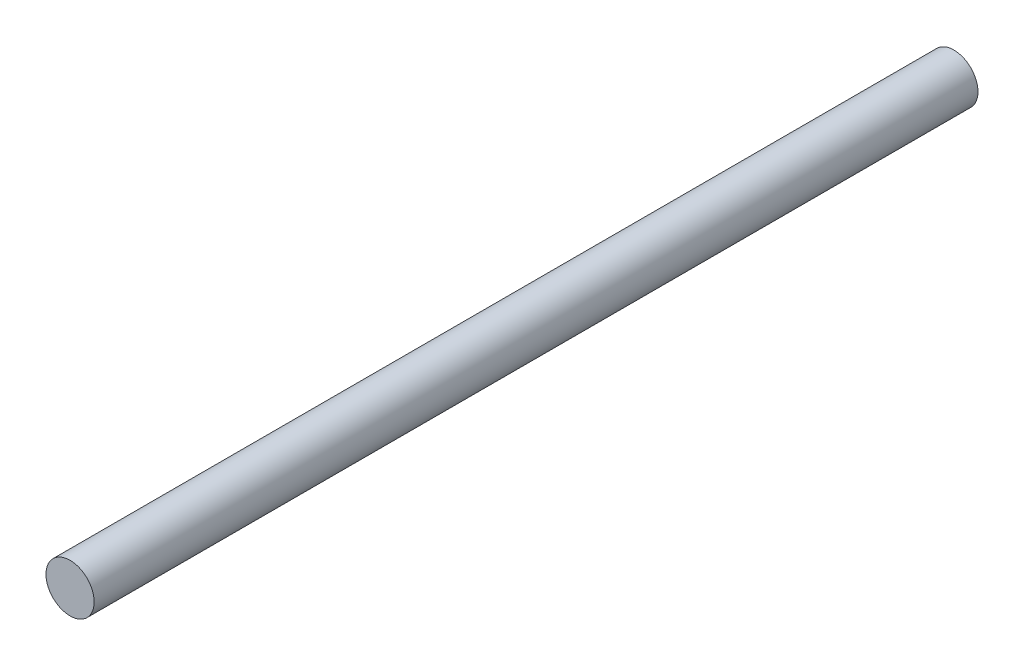
SolidWorks part; units mm, degrees
ref_plane "前基準面" through (0, 0, 0) normal (0, 0, 1) x (1, 0, 0)
ref_plane "上基準面" through (0, 0, 0) normal (0, 1, 0) x (1, 0, 0)
ref_plane "右基準面" through (0, 0, 0) normal (1, 0, 0) x (0, 0, -1)
sketch "草圖1" plane through (0, 0, 0) normal (0, 0, 1) x (1, 0, 0)
  circle A0 centre (0, 0) radius 3
  dimension "D1" = 6
extrude "填料-伸長1" add sketch "草圖1" along normal blind 110
